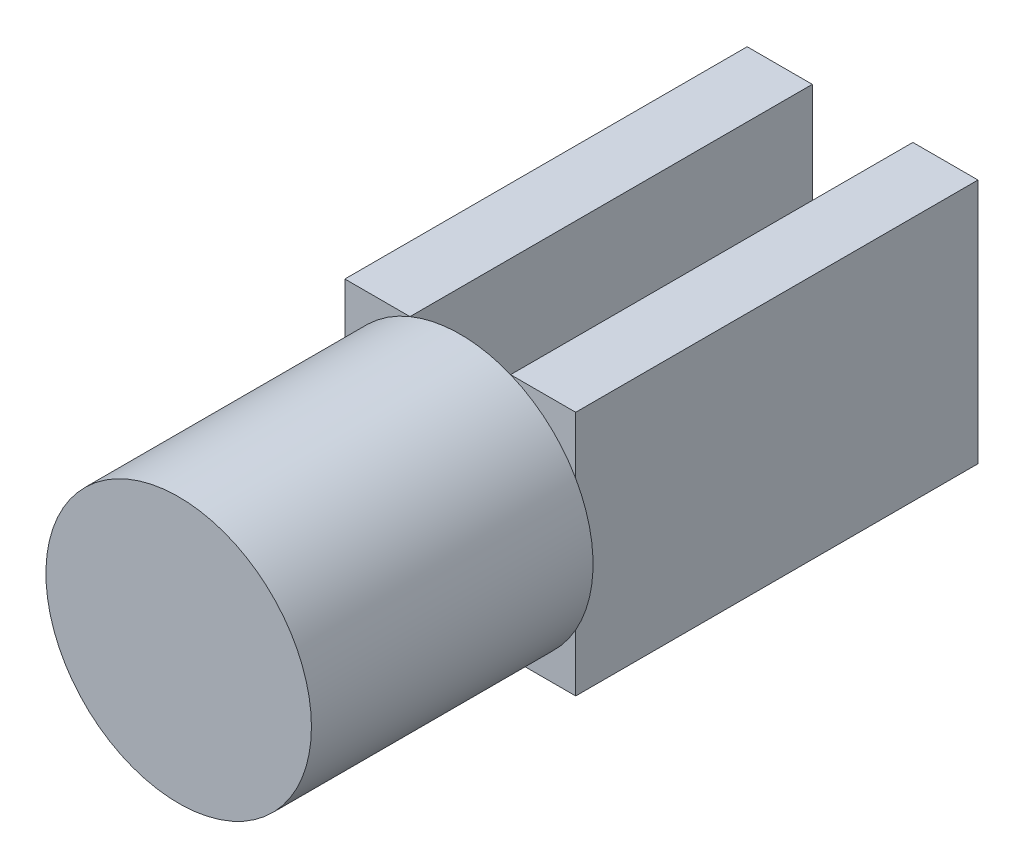
SolidWorks part; units mm, degrees
ref_plane "前视基准面" through (0, 0, 0) normal (0, 0, 1) x (1, 0, 0)
ref_plane "上视基准面" through (0, 0, 0) normal (0, 1, 0) x (1, 0, 0)
ref_plane "右视基准面" through (0, 0, 0) normal (1, 0, 0) x (0, 0, -1)
other "Configuration Table"
sketch "草图1" plane through (0, 0, 0) normal (0, 0, 1) x (1, 0, 0)
  line L0 (0, 33) -> (0, -33) construction
  circle A0 centre (0, 0) radius 33
  dimension "D1" = 66
extrude "凸台-拉伸1" add sketch "草图1" along normal blind 70
sketch "草图2" plane through (0, 0, 0) normal (0, 0, -1) x (-1, 0, 0)
  line L0 (-12.5, 0) -> (12.5, 0) construction
  line L1 (-12.5, 30.541) -> (-12.5, -30.541) construction
  line L2 (12.5, 30.541) -> (12.5, -30.541) construction
  line L3 (0, 0) -> (0, 33) construction
  line L4 (-12.5, 30.541) -> (-28.6906, 30.541)
  line L5 (-12.5, 30.541) -> (-12.5, -30.541)
  line L6 (-12.5, -30.541) -> (-28.6906, -30.541)
  line L7 (-28.6906, 30.541) -> (-28.6906, -30.541)
  line L8 (12.5, 30.541) -> (12.5, -30.541)
  line L9 (12.5, -30.541) -> (28.6906, -30.541)
  line L10 (28.6906, 30.541) -> (28.6906, -30.541)
  line L11 (12.5, 30.541) -> (28.6906, 30.541)
  circle A0 centre (0, 0) radius 12.5
  circle A1 centre (0, 0) radius 33 construction
  dimension "D1" = 25
extrude "凸台-拉伸3" add sketch "草图2" along normal blind 100 contours L4 L7 L6 L5 | L11 L10 L9 L8
